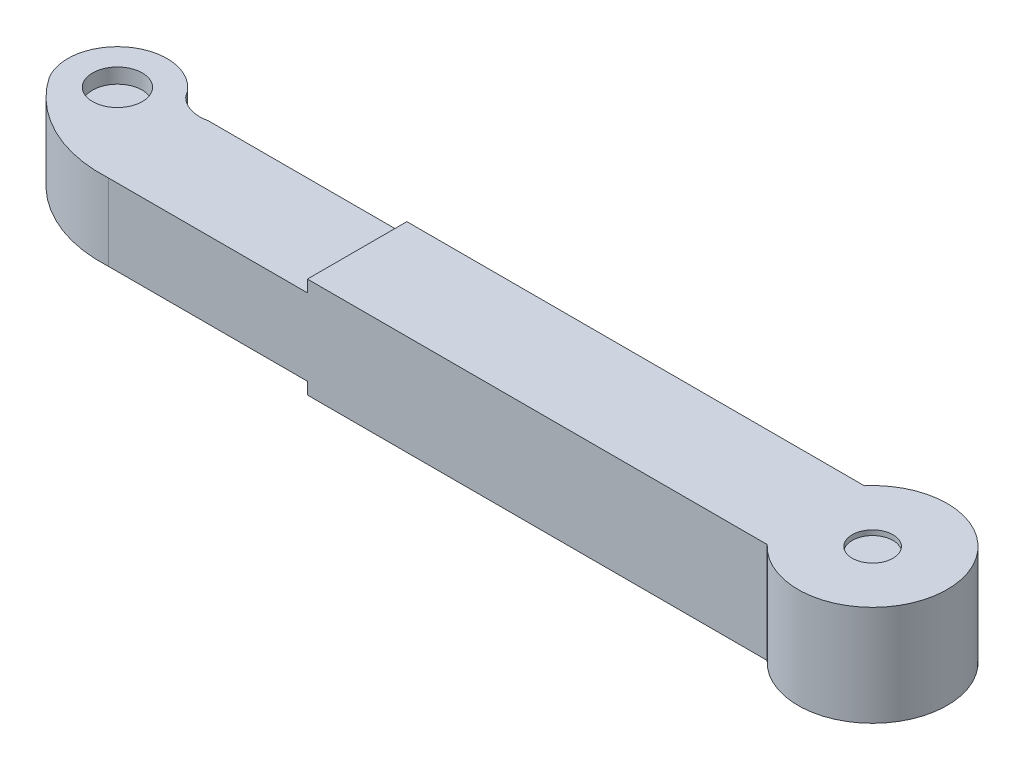
SolidWorks part; units mm, degrees
ref_plane "Alzado" through (0, 0, 0) normal (0, 0, 1) x (1, 0, 0)
ref_plane "Planta" through (0, 0, 0) normal (0, 1, 0) x (1, 0, 0)
ref_plane "Vista lateral" through (0, 0, 0) normal (1, 0, 0) x (0, 0, -1)
sketch "Croquis3" plane through (0, 0, 0) normal (0, 1, 0) x (1, 0, 0)
  line L1 (33.3628, -5.02) -> (-32.8682, -5.02)
  line L3 (33.1318, 4.98) -> (-32.8682, 4.98)
  line L5 (0, 0) -> (-32.8682, 4.98) construction
  line L6 (0, 0) -> (-32.8682, -5.02) construction
  line L7 (-32.8682, 4.98) -> (-32.8682, -5.02)
  arc A1 (33.1318, 4.98) -> (33.3628, -5.02) centre (38.8348, 0.1091) cw
  point P0 (0, 0)
  dimension "D3" = 10
  dimension "D2" = 7.5
  dimension "D1" = 66
extrude "Saliente-Extruir1" add sketch "Croquis3" along normal blind 10.1
sketch "Croquis4" plane through (0, 0, 5.02) normal (0, 0, 1) x (1, 0, 0)
  line L1 (-32.8682, 10.1) -> (-12.8682, 10.1)
  line L2 (-32.8682, 10.1) -> (-32.8682, 8.9)
  line L3 (-32.8682, 8.9) -> (-12.8682, 8.9)
  line L4 (-12.8682, 10.1) -> (-12.8682, 8.9)
  dimension "D1" = 1.2
  dimension "D2" = 20
extrude "Cortar-Extruir1" cut sketch "Croquis4" against normal blind 10
ref_plane "Plano1" through (0, 5.05, 0) normal (0, 1, 0) x (1, 0, 0)
mirror "Simetría1" about plane through (0, 5.05, 0) normal (0, 1, 0) of "Cortar-Extruir1"
sketch "Croquis5" plane through (0, 8.9, 0) normal (0, 1, 0) x (1, 0, 0)
  line L0 (-32.8682, 4.98) -> (-32.8682, -5.02) construction
  line L1 (-32.8682, -5.02) -> (-12.8682, -5.02) construction
  line L2 (-32.8682, 4.98) -> (-32.8682, -5.02)
  arc A0 (-32.8682, -0.02) -> (-40.3232, 3.3307) centre (-33.628, 8.2583) cw construction
  arc A1 (-44.6041, 0.7473) -> (-32.8682, -5.02) centre (-33.628, 8.2583) ccw
  arc A2 (-36.0422, 5.914) -> (-32.8682, 4.98) centre (-33.628, 8.2583) ccw
  arc A3 (-36.0422, 5.914) -> (-44.6041, 0.7473) centre (-40.3232, 3.3307) ccw
  point P3 (-37.1005, 1.1975)
  point P10 (-44.536, 1.1975)
  point P11 (0, 0)
  point P15 (-44.6041, 0.7473)
  dimension "D1" = 5
  dimension "D2" = 13.3
extrude "Saliente-Extruir2" add sketch "Croquis5" against normal up to vertex
sketch "Croquis6" plane through (0, 8.9, 0) normal (0, 1, 0) x (1, 0, 0)
  circle A0 centre (-40.3232, 3.3307) radius 2.5
  dimension "D1" = 5
extrude "Cortar-Extruir2" cut sketch "Croquis6" against normal blind 1.5
mirror "Simetría2" about plane through (0, 5.05, 0) normal (0, 1, 0) of "Cortar-Extruir2"
sketch "Croquis7" plane through (0, 10.1, 0) normal (0, 1, 0) x (1, 0, 0)
  circle A0 centre (38.8348, 0.1091) radius 2.05
  dimension "D1" = 4.1
extrude "Cortar-Extruir3" cut sketch "Croquis7" against normal blind 0.5
